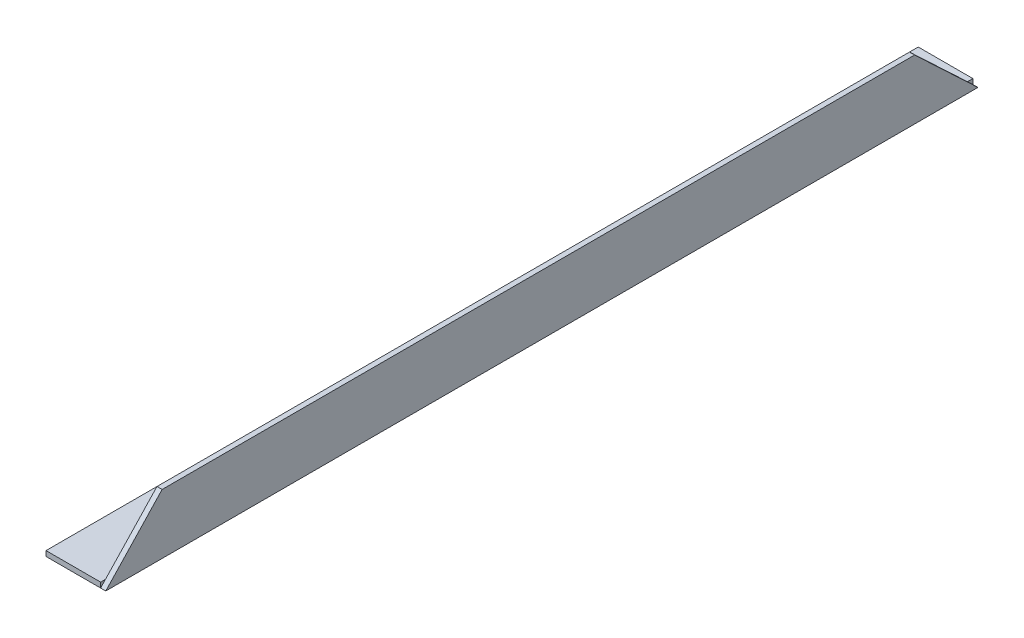
SolidWorks part; units mm, degrees
ref_plane "Front Plane" through (0, 0, 0) normal (0, 0, 1) x (1, 0, 0)
ref_plane "Top Plane" through (0, 0, 0) normal (0, 1, 0) x (1, 0, 0)
ref_plane "Right Plane" through (0, 0, 0) normal (1, 0, 0) x (0, 0, -1)
sketch "Sketch1" plane through (0, 0, 0) normal (1, 0, 0) x (0, 0, -1)
  line L0 (-198.982, 0) -> (141.018, 0)
  line L1 (141.018, 0) -> (116.3002, 23.3)
  line L2 (116.3002, 23.3) -> (-177.0185, 23.3)
  line L3 (-177.0185, 23.3) -> (-198.982, 0)
  line L4 (-30.3591, 23.3) -> (-28.982, 0) construction
  dimension "D1" = 340
  dimension "D2" = 23.3
extrude "Boss-Extrude1" add sketch "Sketch1" along normal blind 2
sketch "Sketch2" plane through (0, 0, 0) normal (-1, 0, 0) x (0, 0, 1)
  line L0 (177.0185, 23.3) -> (198.982, 0) construction
  line L1 (-141.018, 0) -> (198.982, 0)
  line L2 (-141.018, 0) -> (-141.018, 2)
  line L3 (-141.018, 2) -> (198.982, 2)
  line L4 (198.982, 0) -> (198.982, 2)
  line L5 (198.982, 0) -> (-141.018, 0) construction
  dimension "D1" = 2
extrude "Boss-Extrude2" add sketch "Sketch2" along normal blind 21.3
